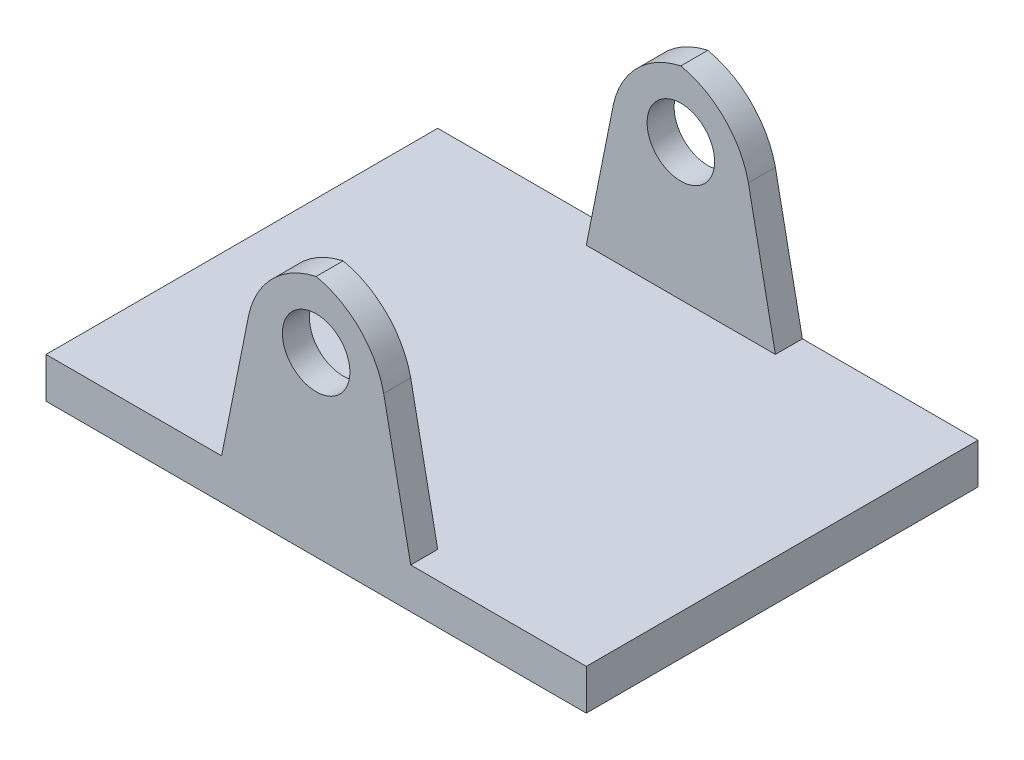
SolidWorks part; units mm, degrees
ref_plane "Front Plane" through (0, 0, 0) normal (0, 0, 1) x (1, 0, 0)
ref_plane "Top Plane" through (0, 0, 0) normal (0, 1, 0) x (1, 0, 0)
ref_plane "Right Plane" through (0, 0, 0) normal (1, 0, 0) x (0, 0, -1)
sketch "Sketch1" plane through (0, 0, 0) normal (0, 0, 1) x (1, 0, 0)
  line L1 (-200, -15) -> (200, -15)
  line L2 (-200, -15) -> (-200, 15)
  line L3 (-200, 15) -> (200, 15)
  line L4 (200, -15) -> (200, 15)
  line L5 (-200, -15) -> (200, 15) construction
  line L6 (-200, 15) -> (200, -15) construction
  point P0 (0, 0)
  dimension "D1" = 400
  dimension "D2" = 30
extrude "Boss-Extrude1" add sketch "Sketch1" along normal blind 290
sketch "Sketch2" plane through (0, 0, 290) normal (0, 0, 1) x (1, 0, 0)
  line L0 (0, 15) -> (0, 165)
  line L1 (200, 15) -> (-200, 15) construction
  line L2 (0, 165) -> (0, 115)
  line L3 (0, 115) -> (-50, 115)
  line L4 (0, 115) -> (50, 115)
  line L5 (-200, 15) -> (-70, 15)
  line L6 (-70, 15) -> (-50, 115)
  line L7 (70, 15) -> (50, 115)
  arc A0 (-50, 115) -> (0, 165) centre (13.7753, 101.2247) cw
  arc A1 (50, 115) -> (0, 165) centre (-13.7753, 101.2247) ccw
  line M7 (200, 15) -> (-200, 15)
  dimension "D1" = 50
  dimension "D2" = 150
  dimension "D3" = 50
  dimension "D5" = 130
extrude "Boss-Extrude2" add sketch "Sketch2" against normal blind 20 contours L4 A1 L0 | A0 L3 L0 | L6 L0 L3 M7 | L7 L4 L0 M7
sketch "Sketch4" plane through (0, 0, 290) normal (0, 0, 1) x (1, 0, 0)
  circle A0 centre (0, 116.0921) radius 25
extrude "Cut-Extrude1" cut sketch "Sketch4" against normal blind 20
sketch "Sketch5" plane through (0, 0, 0) normal (0, 0, -1) x (-1, 0, 0)
  line L0 (-70, 15) -> (-50, 115)
  line L1 (70, 15) -> (50, 115)
  line L2 (-70, 15) -> (70, 15)
  arc A0 (-50, 115) -> (0, 165) centre (13.7753, 101.2247) cw
  arc A1 (0, 165) -> (-50, 115) centre (13.7753, 101.2247) ccw construction
  arc A2 (0, 165) -> (50, 115) centre (-13.7753, 101.2247) cw
  circle A3 centre (0, 116.0921) radius 25
extrude "Boss-Extrude3" add sketch "Sketch5" against normal blind 20
